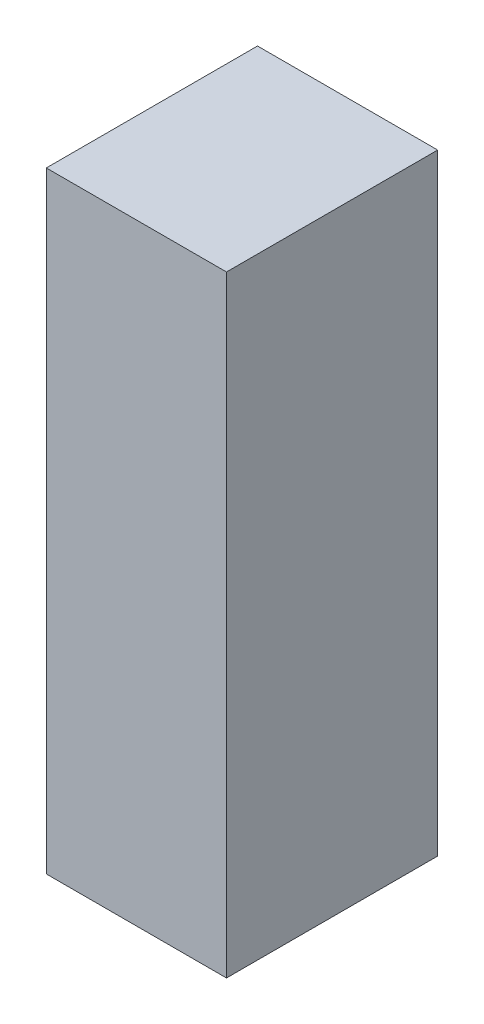
SolidWorks part; units mm, degrees
ref_plane "Front Plane" through (0, 0, 0) normal (0, 0, 1) x (1, 0, 0)
ref_plane "Top Plane" through (0, 0, 0) normal (0, 1, 0) x (1, 0, 0)
ref_plane "Right Plane" through (0, 0, 0) normal (1, 0, 0) x (0, 0, -1)
sketch "Sketch1" plane through (0, 0, 0) normal (0, 1, 0) x (1, 0, 0)
  line L1 (0, 0) -> (309.88, 0)
  line L2 (0, 0) -> (0, 363.22)
  line L3 (0, 363.22) -> (309.88, 363.22)
  line L4 (309.88, 0) -> (309.88, 363.22)
  dimension "D1" = 309.88
  dimension "D2" = 363.22
extrude "Boss-Extrude1" add sketch "Sketch1" along normal blind 1051.56
ref_point "Point1"
